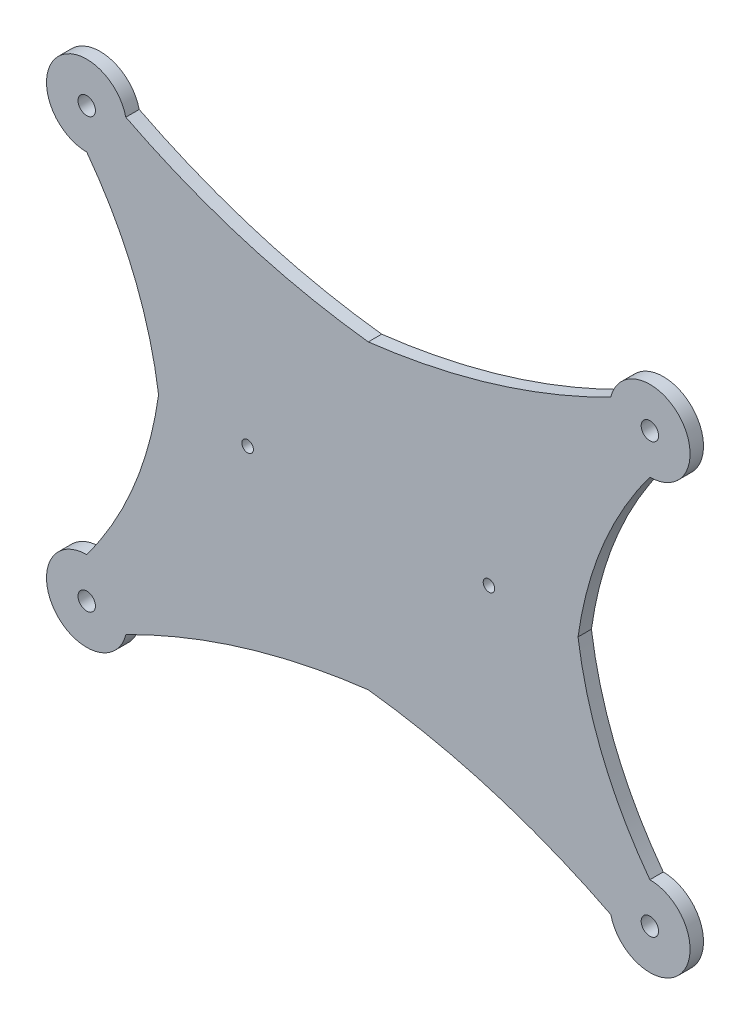
SolidWorks part; units mm, degrees
ref_plane "Front Plane" through (0, 0, 0) normal (0, 0, 1) x (1, 0, 0)
ref_plane "Top Plane" through (0, 0, 0) normal (0, 1, 0) x (1, 0, 0)
ref_plane "Right Plane" through (0, 0, 0) normal (1, 0, 0) x (0, 0, -1)
sketch3d "Sketch1"
  circle A0 centre (-91.7521, 22.3539, 0) radius 2.15
  circle A1 centre (-1.7521, 22.3539, 0) radius 2.15
  circle A2 centre (58.2479, 102.3539, 0) radius 3.25
  circle A3 centre (58.2479, -57.6461, 0) radius 3.25
  circle A4 centre (-151.7521, 102.3539, 0) radius 3.25
  circle A5 centre (-151.7521, -57.6461, 0) radius 3.25
  arc A6 (58.2479, 87.3539, 0) -> (43.6706, 105.8901, 0) centre (58.2479, 102.3539, 0) ccw
  arc A7 (43.6706, -61.1822, 0) -> (58.2479, -42.6461, 0) centre (58.2479, -57.6461, 0) ccw
  arc A8 (-151.7521, -42.6461, 0) -> (-137.1749, -61.1822, 0) centre (-151.7521, -57.6461, 0) ccw
  arc A9 (-137.1749, 105.8901, 0) -> (-151.7521, 87.3539, 0) centre (-151.7521, 102.3539, 0) ccw
  spline S0 degree 3 poles (43.6706, 105.8901, 0) (15.1728, 91.4379, 0) (-14.9681, 82.321, 0) (-46.7521, 78.5393, 0) knots 0 0 0 0 1 1 1 1 weights 1 1 1 1
  spline S1 degree 3 poles (31.451, 22.3539, 0) (34.8146, 46.1703, 0) (43.7469, 67.837, 0) (58.2479, 87.3539, 0) knots 0 0 0 0 1 1 1 1 weights 1 1 1 1
  spline S2 degree 3 poles (58.2479, -42.6461, 0) (43.7469, -23.1291, 0) (34.8146, -1.4624, 0) (31.451, 22.3539, 0) knots 0 0 0 0 1 1 1 1 weights 1 1 1 1
  spline S3 degree 3 poles (-46.7521, -33.8314, 0) (-14.9681, -37.6131, 0) (15.1728, -46.7301, 0) (43.6706, -61.1822, 0) knots 0 0 0 0 1 1 1 1 weights 1 1 1 1
  spline S4 degree 3 poles (-137.1749, -61.1822, 0) (-108.677, -46.7301, 0) (-78.5361, -37.6131, 0) (-46.7521, -33.8314, 0) knots 0 0 0 0 1 1 1 1 weights 1 1 1 1
  spline S5 degree 3 poles (-124.9552, 22.3539, 0) (-128.3189, -1.4624, 0) (-137.2512, -23.1291, 0) (-151.7521, -42.6461, 0) knots 0 0 0 0 1 1 1 1 weights 1 1 1 1
  spline S6 degree 3 poles (-151.7521, 87.3539, 0) (-137.2512, 67.837, 0) (-128.3189, 46.1703, 0) (-124.9552, 22.3539, 0) knots 0 0 0 0 1 1 1 1 weights 1 1 1 1
  spline S7 degree 3 poles (-46.7521, 78.5393, 0) (-78.5361, 82.321, 0) (-108.677, 91.4379, 0) (-137.1749, 105.8901, 0) knots 0 0 0 0 1 1 1 1 weights 1 1 1 1
  point P2 (-91.7521, 22.3539, 2.15)
  point P5 (-1.7521, 22.3539, 2.15)
  point P8 (58.2479, 102.3539, 3.25)
  point P11 (58.2479, -57.6461, 3.25)
  point P14 (-151.7521, 102.3539, 3.25)
  point P17 (-151.7521, -57.6461, 3.25)
  point P30 (58.2479, 102.3539, 15)
  point P31 (58.2479, -57.6461, 15)
  point P32 (-151.7521, -57.6461, 15)
  point P33 (-151.7521, 102.3539, 15)
sketch "Sketch2" plane through (0, 0, 0) normal (0, 0, 1) x (1, 0, 0)
  circle A1 centre (-151.7521, 102.3539) radius 3.25
  circle A2 centre (-151.7521, 102.3539) radius 3.25
  circle A3 centre (58.2479, -57.6461) radius 3.25
  circle A4 centre (58.2479, -57.6461) radius 3.25
  circle A5 centre (58.2479, 102.3539) radius 3.25
  circle A6 centre (58.2479, 102.3539) radius 3.25
  circle A7 centre (-1.7521, 22.3539) radius 2.15
  circle A8 centre (-1.7521, 22.3539) radius 2.15
  circle A9 centre (-91.7521, 22.3539) radius 2.15
  circle A10 centre (-91.7521, 22.3539) radius 2.15
  circle A11 centre (-151.7521, -57.6461) radius 3.25
  circle A12 centre (-151.7521, -57.6461) radius 3.25
  arc A14 (58.2479, 87.3539) -> (43.6706, 105.8901) centre (58.2479, 102.3539) ccw
  arc A15 (-137.1749, 105.8901) -> (-151.7521, 87.3539) centre (-151.7521, 102.3539) ccw
  arc A16 (-151.7521, -42.6461) -> (-137.1749, -61.1822) centre (-151.7521, -57.6461) ccw
  arc A17 (43.6706, -61.1822) -> (58.2479, -42.6461) centre (58.2479, -57.6461) ccw
  arc A18 (58.2479, 87.3539) -> (43.6706, 105.8901) centre (58.2479, 102.3539) ccw
  arc A19 (-137.1749, 105.8901) -> (-151.7521, 87.3539) centre (-151.7521, 102.3539) ccw
  arc A20 (-151.7521, -42.6461) -> (-137.1749, -61.1822) centre (-151.7521, -57.6461) ccw
  arc A21 (43.6706, -61.1822) -> (58.2479, -42.6461) centre (58.2479, -57.6461) ccw
  spline S8 degree 3 poles (132.248, 5030.0297) (963.8713, -1249.216) (-43.002, -1558.604) (-2888.3719, 4101.8657) knots -16.237723 -16.237723 -16.237723 -16.237723 17.212957 17.212957 17.212957 17.212957 weights 1 1 1 1 only from (43.6706, 105.8901) to (-46.7521, 78.5393)
  spline S9 degree 3 poles (2794.8841, 4101.8983) (-50.4854, -1558.5793) (-1057.368, -1249.2309) (-225.7637, 5029.9435) knots -16.213022 -16.213022 -16.213022 -16.213022 17.23757 17.23757 17.23757 17.23757 weights 1 1 1 1 only from (-46.7521, 78.5393) to (-137.1749, 105.8901)
  spline S10 degree 3 poles (-5061.1145, -610.6117) (1230.9142, 993.0259) (1509.5519, 275.2857) (-4225.2015, -2763.8322) knots -15.889922 -15.889922 -15.889922 -15.889922 16.971282 16.971282 16.971282 16.971282 weights 1 1 1 1 only from (-151.7521, 87.3539) to (-124.9552, 22.3539)
  spline S11 degree 3 poles (-4225.2157, 2808.5476) (1509.5448, -230.5727) (1230.9201, -948.3174) (-5061.0897, 655.3133) knots -15.971309 -15.971309 -15.971309 -15.971309 16.889879 16.889879 16.889879 16.889879 weights 1 1 1 1 only from (-124.9552, 22.3539) to (-151.7521, -42.6461)
  spline S12 degree 3 poles (-225.7522, -4985.3218) (-1057.3756, 1293.9239) (-50.5023, 1603.3119) (2794.8676, -4057.1578) knots -16.237723 -16.237723 -16.237723 -16.237723 17.212957 17.212957 17.212957 17.212957 weights 1 1 1 1 only from (-137.1749, -61.1822) to (-46.7521, -33.8314)
  spline S13 degree 3 poles (-2888.3883, -4057.1905) (-43.0189, 1603.2872) (963.8637, 1293.9388) (132.2594, -4985.2356) knots -16.213022 -16.213022 -16.213022 -16.213022 17.23757 17.23757 17.23757 17.23757 weights 1 1 1 1 only from (-46.7521, -33.8314) to (43.6706, -61.1822)
  spline S14 degree 3 poles (4967.6103, 655.3196) (-1324.4184, -948.318) (-1603.0561, -230.5778) (4131.6972, 2808.5401) knots -15.889922 -15.889922 -15.889922 -15.889922 16.971282 16.971282 16.971282 16.971282 weights 1 1 1 1 only from (58.2479, -42.6461) to (31.451, 22.3539)
  spline S15 degree 3 poles (4131.7114, -2763.8397) (-1603.0491, 275.2805) (-1324.4244, 993.0253) (4967.5855, -610.6054) knots -15.971309 -15.971309 -15.971309 -15.971309 16.889879 16.889879 16.889879 16.889879 weights 1 1 1 1 only from (31.451, 22.3539) to (58.2479, 87.3539)
  spline S16 degree 3 poles (43.6706, 105.8901) (15.1728, 91.4379) (-14.9681, 82.321) (-46.7521, 78.5393) knots 0 0 0 0 1 1 1 1 weights 1 1 1 1
  spline S17 degree 3 poles (-46.7521, 78.5393) (-78.5361, 82.321) (-108.677, 91.4379) (-137.1749, 105.8901) knots 0 0 0 0 1 1 1 1 weights 1 1 1 1
  spline S18 degree 3 poles (-151.7521, 87.3539) (-137.2512, 67.837) (-128.3189, 46.1703) (-124.9552, 22.3539) knots 0 0 0 0 1 1 1 1 weights 1 1 1 1
  spline S19 degree 3 poles (-124.9552, 22.3539) (-128.3189, -1.4624) (-137.2512, -23.1291) (-151.7521, -42.6461) knots 0 0 0 0 1 1 1 1 weights 1 1 1 1
  spline S20 degree 3 poles (-137.1749, -61.1822) (-108.677, -46.7301) (-78.5361, -37.6131) (-46.7521, -33.8314) knots 0 0 0 0 1 1 1 1 weights 1 1 1 1
  spline S21 degree 3 poles (-46.7521, -33.8314) (-14.9681, -37.6131) (15.1728, -46.7301) (43.6706, -61.1822) knots 0 0 0 0 1 1 1 1 weights 1 1 1 1
  spline S22 degree 3 poles (58.2479, -42.6461) (43.7469, -23.1291) (34.8146, -1.4624) (31.451, 22.3539) knots 0 0 0 0 1 1 1 1 weights 1 1 1 1
  spline S23 degree 3 poles (31.451, 22.3539) (34.8146, 46.1703) (43.7469, 67.837) (58.2479, 87.3539) knots 0 0 0 0 1 1 1 1 weights 1 1 1 1
  dimension "D1" = 0
  dimension "D2" = 0
  dimension "D3" = 0
  dimension "D4" = 0
  dimension "D5" = 0
  dimension "D6" = 0
  dimension "D7" = 0
extrude "Boss-Extrude1" add sketch "Sketch2" along normal blind 5
